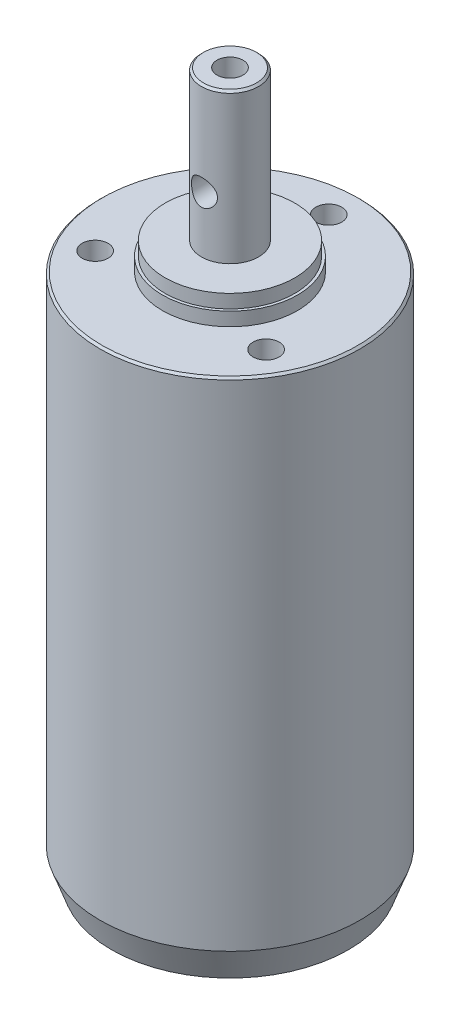
SolidWorks part; units mm, degrees
ref_plane "前视基准面" through (0, 0, 0) normal (0, 0, 1) x (1, 0, 0)
ref_plane "上视基准面" through (0, 0, 0) normal (0, 1, 0) x (1, 0, 0)
ref_plane "右视基准面" through (0, 0, 0) normal (1, 0, 0) x (0, 0, -1)
sketch "草图1" plane through (0, 0, 0) normal (1, 0, 0) x (0, 0, -1)
  line L0 (0, 90.0419) -> (0, -172.9611) construction
  line L1 (0, 0) -> (2.75, 0)
  line L2 (2.75, 0) -> (2.75, 4)
  line L3 (2.75, 4) -> (12.5, 4)
  line L4 (12.5, 4) -> (12.5, 54.8)
  line L5 (12.5, 54.8) -> (6.5, 54.8)
  line L6 (6.5, 54.8) -> (6.5, 56.1)
  line L7 (6.2386, 57.4) -> (2.75, 57.4)
  line L8 (2.75, 57.4) -> (2.75, 71.8)
  line L9 (2.75, 71.8) -> (0, 71.8)
  line L10 (0, 71.8) -> (0, 0)
  line L11 (6.2386, 57.4) -> (6.2386, 56.1)
  line L12 (6.2386, 56.1) -> (6.5, 56.1)
  dimension "D1" = 71.8
  dimension "D2" = 2.75
  dimension "D3" = 2.75
  dimension "D4" = 6.5
  dimension "D5" = 12.5
  dimension "D6" = 17
  dimension "D7" = 2.6
  dimension "D8" = 50.8
revolve "旋转1" add sketch "草图1" angle 360 about L0
chamfer "倒角1" distance 0.2 angle 45 2 edges at (0, 0, 2.75) (0, 54.8, 12.5)
chamfer "倒角2" distance 3 angle 20 1 edges at (0, 4, 12.5)
hole_wizard "M3 螺纹孔1" positions "草图2" profile "草图3" tap size "M3" standard "GB"
sketch "草图2" plane through (0, 71.8, 0) normal (0, 1, 0) x (1, 0, 0)
  point P0 (0, 0)
sketch "草图3" plane through (0, 71.8, 0) normal (1, 0, 0) x (0, 0, 1)
  line L0 (0, 0) -> (0, 6.2511)
  line L1 (0, 6.2511) -> (1.25, 5.5)
  line L2 (1.25, 5.5) -> (1.25, 0)
  line L5 (1.25, 0) -> (0, 0)
  line L10 (0, 6.2511) -> (-1.25, 5.5) construction
  line L11 (0, -6.35) -> (0, 107.95) construction
  dimension "螺纹孔钻头直径" = 2.5
  dimension "螺纹孔钻头深度" = 5.5
  dimension "导头角度" = 118
cosmetic thread "孔螺蚊线1" parameters "D1"=5, "D2"=3
ref_plane "基准面1" through (0, 0, 2.75) normal (0, 0, 1) x (1, 0, 0)
sketch "草图4" plane through (0, 0, 2.75) normal (0, 0, 1) x (1, 0, 0)
  line L0 (0, 71.8) -> (0, 62.8) construction
  line L1 (2.55, 71.8) -> (-2.55, 71.8) construction
  point P6 (0, 62.8)
  dimension "D1" = 9
hole_wizard "M3 螺纹孔2" positions "草图7" profile "草图8" tap size "M3" standard "GB"
sketch "草图7" plane through (0, 0, 2.75) normal (0, 0, 1) x (1, 0, 0)
  point P0 (0, 62.8)
sketch "草图8" plane through (0, 62.8, 2.75) normal (1, 0, 0) x (0, -1, 0)
  line L0 (0, 0) -> (0, 8.2511)
  line L1 (0, 8.2511) -> (1.25, 7.5)
  line L2 (1.25, 7.5) -> (1.25, 0)
  line L5 (1.25, 0) -> (0, 0)
  line L10 (0, 8.2511) -> (-1.25, 7.5) construction
  line L11 (0, -6.35) -> (0, 107.95) construction
  dimension "螺纹孔钻头直径" = 2.5
  dimension "螺纹孔钻头深度" = 7.5
  dimension "导头角度" = 118
cosmetic thread "孔螺蚊线2" parameters "D1"=5, "D2"=3
sketch "草图9" plane through (0, 54.8, 0) normal (0, 1, 0) x (1, 0, 0)
  line L0 (0, 9.5) -> (0, 0) construction
  line L1 (0, 0) -> (8.2272, -4.75) construction
  line L2 (0, 0) -> (-8.2272, -4.75) construction
  circle A0 centre (0, 0) radius 9.5 construction
  dimension "D1" = 19
  dimension "D2" = 120
  dimension "D3" = 120
hole_wizard "M3 螺纹孔3" positions "草图10" profile "草图11" tap size "M3" standard "GB"
sketch "草图10" plane through (0, 54.8, 0) normal (0, 1, 0) x (1, 0, 0)
  point P0 (0, 9.5)
  point P3 (-8.2272, -4.75)
  point P6 (8.2272, -4.75)
sketch "草图11" plane through (0, 54.8, -9.5) normal (1, 0, 0) x (0, 0, 1)
  line L0 (0, 0) -> (0, 4.7511)
  line L1 (0, 4.7511) -> (1.25, 4)
  line L2 (1.25, 4) -> (1.25, 0)
  line L5 (1.25, 0) -> (0, 0)
  line L10 (0, 4.7511) -> (-1.25, 4) construction
  line L11 (0, -6.35) -> (0, 107.95) construction
  dimension "螺纹孔钻头直径" = 2.5
  dimension "螺纹孔钻头深度" = 4
  dimension "导头角度" = 118
cosmetic thread "孔螺蚊线3" parameters "D1"=3.5, "D2"=3
cosmetic thread "孔螺蚊线4" parameters "D1"=3.5, "D2"=3
cosmetic thread "孔螺蚊线5" parameters "D1"=3.5, "D2"=3
